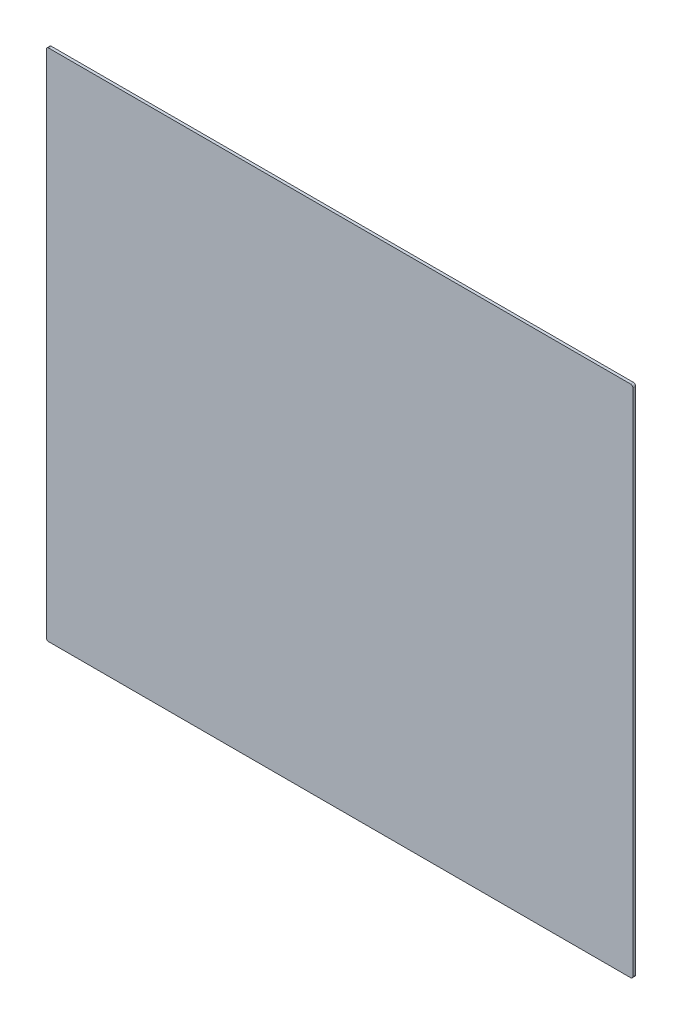
SolidWorks part; units mm, degrees
ref_plane "Front Plane" through (0, 0, 0) normal (0, 0, 1) x (1, 0, 0)
ref_plane "Top Plane" through (0, 0, 0) normal (0, 1, 0) x (1, 0, 0)
ref_plane "Right Plane" through (0, 0, 0) normal (1, 0, 0) x (0, 0, -1)
sketch "Sketch1" plane through (0, 0, 0) normal (0, 0, 1) x (1, 0, 0)
  line L1 (-224.9767, 260.7264) -> (422.7233, 260.7264)
  line L2 (-224.9767, 260.7264) -> (-224.9767, -306.9636)
  line L3 (-224.9767, -306.9636) -> (422.7233, -306.9636)
  line L4 (422.7233, 260.7264) -> (422.7233, -306.9636)
  dimension "D1" = 567.69
  dimension "D2" = 647.7
extrude "Boss-Extrude1" add sketch "Sketch1" along normal blind 3.175 contours L2 L3 L4 L1
fillet "Fillet1" radius 2.54 4 edges at (-224.9767, -306.9636, 1.5875) (422.7233, -306.9636, 1.5875) (422.7233, 260.7264, 1.5875) (-224.9767, 260.7264, 1.5875)
